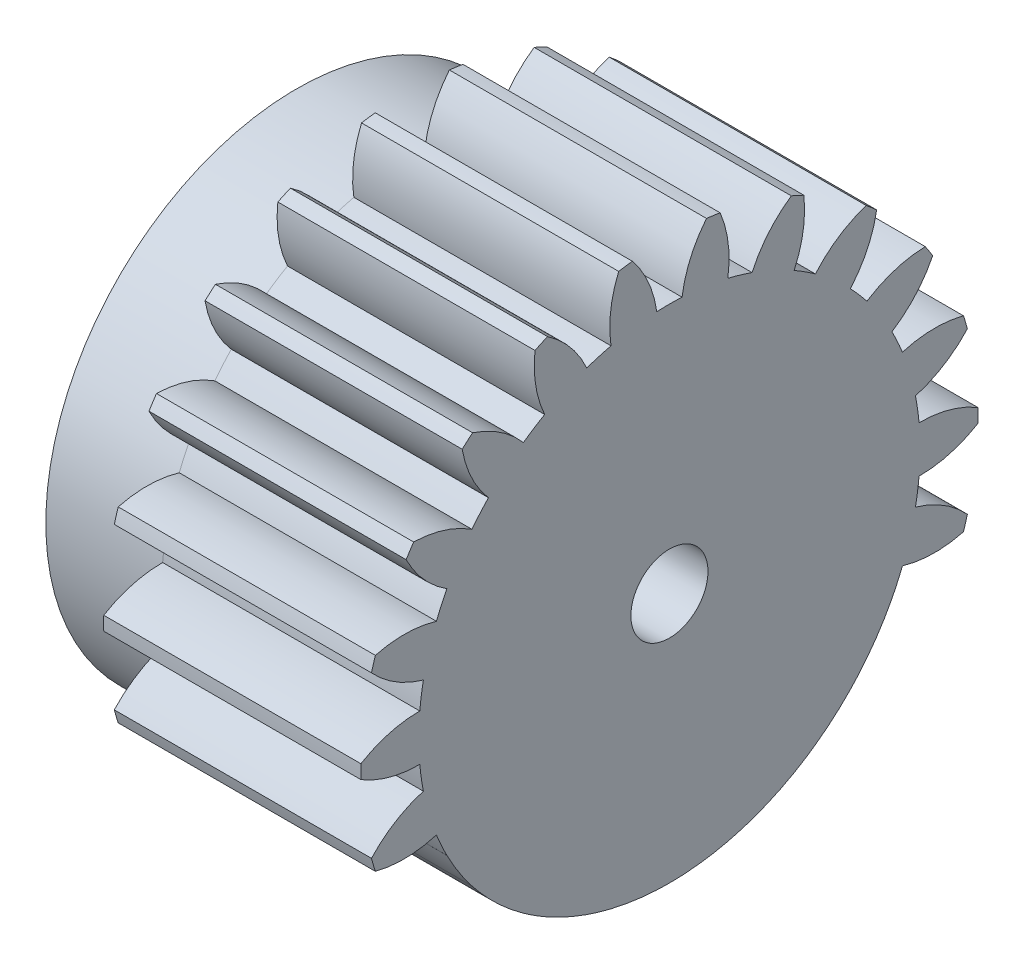
SolidWorks part; units mm, degrees
ref_plane "Front Plane" through (0, 0, 0) normal (0, 0, 1) x (1, 0, 0)
ref_plane "Top Plane" through (0, 0, 0) normal (0, 1, 0) x (1, 0, 0)
ref_plane "Right Plane" through (0, 0, 0) normal (1, 0, 0) x (0, 0, -1)
ref_plane "Plane2" through (4.0389, 0, 0) normal (1, 0, 0) x (0, 0, -1)
sketch "Sketch5" plane through (4.0389, 0, 0) normal (1, 0, 0) x (0, 0, -1)
  circle A0 centre (3.23, 4.4522) radius 1.5
  arc A1 (-8.767, 4.1839) -> (-6.4774, 3.5525) centre (-6.496, 7.9525) ccw
  arc A2 (-6.4774, 3.5525) -> (-6.3377, 2.5805) centre (3.23, 4.4522) ccw
  arc A3 (-6.3377, 2.5805) -> (-8.3567, 1.3296) centre (-5.1159, -1.6464) ccw
  arc A4 (-8.3567, 1.3296) -> (-8.2055, 0.8148) centre (3.23, 4.4522) ccw
  arc A5 (-8.2055, 0.8148) -> (-5.8308, 0.8541) centre (-7.0882, 5.0706) ccw
  arc A6 (-5.8308, 0.8541) -> (-5.4228, -0.0392) centre (3.23, 4.4522) ccw
  arc A7 (-5.4228, -0.0392) -> (-7.0076, -1.8082) centre (-3.0596, -3.7507) ccw
  arc A8 (-7.0076, -1.8082) -> (-6.7175, -2.2596) centre (3.23, 4.4522) ccw
  arc A9 (-6.7175, -2.2596) -> (-4.45, -1.5529) centre (-6.8444, 2.1386) ccw
  arc A10 (-4.45, -1.5529) -> (-3.807, -2.295) centre (3.23, 4.4522) ccw
  arc A11 (-3.807, -2.295) -> (-4.8292, -4.4389) centre (-0.4938, -5.1904) ccw
  arc A12 (-4.8292, -4.4389) -> (-4.4237, -4.7902) centre (3.23, 4.4522) ccw
  arc A13 (-4.4237, -4.7902) -> (-2.4471, -3.4733) centre (-5.7845, -0.606) ccw
  arc A14 (-2.4471, -3.4733) -> (-1.621, -4.0043) centre (3.23, 4.4522) ccw
  arc A15 (-1.621, -4.0043) -> (-1.9978, -6.3492) centre (2.3736, -5.8489) ccw
  arc A16 (-1.9978, -6.3492) -> (-1.5097, -6.5721) centre (3.23, 4.4522) ccw
  arc A17 (-1.5097, -6.5721) -> (0.0157, -4.7517) centre (-3.9943, -2.9408) ccw
  arc A18 (0.0157, -4.7517) -> (0.9579, -5.0284) centre (3.23, 4.4522) ccw
  arc A19 (0.9579, -5.0284) -> (1.257, -7.3845) centre (5.3105, -5.6729) ccw
  arc A20 (1.257, -7.3845) -> (1.7882, -7.4609) centre (3.23, 4.4522) ccw
  arc A21 (1.7882, -7.4609) -> (2.739, -5.2845) centre (-1.6189, -4.6766) ccw
  arc A22 (2.739, -5.2845) -> (3.721, -5.2845) centre (3.23, 4.4522) ccw
  arc A23 (3.721, -5.2845) -> (4.6718, -7.4609) centre (8.0788, -4.6766) ccw
  arc A24 (4.6718, -7.4609) -> (5.2029, -7.3845) centre (3.23, 4.4522) ccw
  arc A25 (5.2029, -7.3845) -> (5.502, -5.0284) centre (1.1494, -5.6729) ccw
  arc A26 (5.502, -5.0284) -> (6.4442, -4.7517) centre (3.23, 4.4522) ccw
  arc A27 (6.4442, -4.7517) -> (7.9696, -6.5721) centre (10.4542, -2.9408) ccw
  arc A28 (7.9696, -6.5721) -> (8.4577, -6.3492) centre (3.23, 4.4522) ccw
  arc A29 (8.4577, -6.3492) -> (8.0809, -4.0043) centre (4.0863, -5.8489) ccw
  arc A30 (8.0809, -4.0043) -> (8.907, -3.4733) centre (3.23, 4.4522) ccw
  arc A31 (8.907, -3.4733) -> (10.8836, -4.7902) centre (12.2444, -0.606) ccw
  arc A32 (10.8836, -4.7902) -> (11.2891, -4.4389) centre (3.23, 4.4522) ccw
  arc A33 (11.2891, -4.4389) -> (10.2669, -2.295) centre (6.9537, -5.1904) ccw
  arc A34 (10.2669, -2.295) -> (10.9099, -1.5529) centre (3.23, 4.4522) ccw
  arc A35 (10.9099, -1.5529) -> (13.1774, -2.2596) centre (13.3043, 2.1386) ccw
  arc A36 (13.1774, -2.2596) -> (13.4675, -1.8082) centre (3.23, 4.4522) ccw
  arc A37 (13.4675, -1.8082) -> (11.8827, -0.0392) centre (9.5195, -3.7507) ccw
  arc A38 (11.8827, -0.0392) -> (12.2907, 0.8541) centre (3.23, 4.4522) ccw
  arc A39 (12.2907, 0.8541) -> (14.6654, 0.8148) centre (13.5481, 5.0706) ccw
  arc A40 (14.6654, 0.8148) -> (14.8166, 1.3296) centre (3.23, 4.4522) ccw
  arc A41 (14.8166, 1.3296) -> (12.7976, 2.5805) centre (11.5758, -1.6464) ccw
  arc A42 (12.7976, 2.5805) -> (12.9374, 3.5525) centre (3.23, 4.4522) ccw
  arc A43 (12.9374, 3.5525) -> (15.227, 4.1839) centre (12.9559, 7.9525) ccw
  arc A44 (15.227, 4.1839) -> (15.227, 4.7205) centre (3.23, 4.4522) ccw
  arc A45 (15.227, 4.7205) -> (12.9374, 5.3518) centre (12.9559, 0.9519) ccw
  arc A46 (12.9374, 5.3518) -> (12.7976, 6.3238) centre (3.23, 4.4522) ccw
  arc A47 (12.7976, 6.3238) -> (14.8166, 7.5747) centre (11.5758, 10.5508) ccw
  arc A48 (14.8166, 7.5747) -> (14.6654, 8.0895) centre (3.23, 4.4522) ccw
  arc A49 (14.6654, 8.0895) -> (12.2907, 8.0503) centre (13.5481, 3.8338) ccw
  arc A50 (12.2907, 8.0503) -> (11.8827, 8.9435) centre (3.23, 4.4522) ccw
  arc A51 (11.8827, 8.9435) -> (13.4675, 10.7125) centre (9.5195, 12.655) ccw
  arc A52 (13.4675, 10.7125) -> (13.1774, 11.1639) centre (3.23, 4.4522) ccw
  arc A53 (13.1774, 11.1639) -> (10.9099, 10.4572) centre (13.3043, 6.7658) ccw
  arc A54 (10.9099, 10.4572) -> (10.2669, 11.1994) centre (3.23, 4.4522) ccw
  arc A55 (10.2669, 11.1994) -> (11.2891, 13.3432) centre (6.9537, 14.0947) ccw
  arc A56 (11.2891, 13.3432) -> (10.8836, 13.6946) centre (3.23, 4.4522) ccw
  arc A57 (10.8836, 13.6946) -> (8.907, 12.3777) centre (12.2444, 9.5103) ccw
  arc A58 (8.907, 12.3777) -> (8.0809, 12.9086) centre (3.23, 4.4522) ccw
  arc A59 (8.0809, 12.9086) -> (8.4577, 15.2536) centre (4.0863, 14.7533) ccw
  arc A60 (8.4577, 15.2536) -> (7.9696, 15.4765) centre (3.23, 4.4522) ccw
  arc A61 (7.9696, 15.4765) -> (6.4442, 13.6561) centre (10.4542, 11.8451) ccw
  arc A62 (6.4442, 13.6561) -> (5.502, 13.9327) centre (3.23, 4.4522) ccw
  arc A63 (5.502, 13.9327) -> (5.2029, 16.2889) centre (1.1494, 14.5772) ccw
  arc A64 (5.2029, 16.2889) -> (4.6718, 16.3652) centre (3.23, 4.4522) ccw
  arc A65 (4.6718, 16.3652) -> (3.721, 14.1888) centre (8.0788, 13.581) ccw
  arc A66 (3.721, 14.1888) -> (2.739, 14.1888) centre (3.23, 4.4522) ccw
  arc A67 (2.739, 14.1888) -> (1.7882, 16.3652) centre (-1.6189, 13.581) ccw
  arc A68 (1.7882, 16.3652) -> (1.257, 16.2889) centre (3.23, 4.4522) ccw
  arc A69 (1.257, 16.2889) -> (0.9579, 13.9327) centre (5.3105, 14.5772) ccw
  arc A70 (0.9579, 13.9327) -> (0.0157, 13.6561) centre (3.23, 4.4522) ccw
  arc A71 (0.0157, 13.6561) -> (-1.5097, 15.4765) centre (-3.9943, 11.8451) ccw
  arc A72 (-1.5097, 15.4765) -> (-1.9978, 15.2536) centre (3.23, 4.4522) ccw
  arc A73 (-1.9978, 15.2536) -> (-1.621, 12.9086) centre (2.3736, 14.7533) ccw
  arc A74 (-1.621, 12.9086) -> (-2.4471, 12.3777) centre (3.23, 4.4522) ccw
  arc A75 (-2.4471, 12.3777) -> (-4.4237, 13.6946) centre (-5.7845, 9.5103) ccw
  arc A76 (-4.4237, 13.6946) -> (-4.8292, 13.3432) centre (3.23, 4.4522) ccw
  arc A77 (-4.8292, 13.3432) -> (-3.807, 11.1994) centre (-0.4938, 14.0947) ccw
  arc A78 (-3.807, 11.1994) -> (-4.45, 10.4572) centre (3.23, 4.4522) ccw
  arc A79 (-4.45, 10.4572) -> (-6.7175, 11.1639) centre (-6.8444, 6.7658) ccw
  arc A80 (-6.7175, 11.1639) -> (-7.0076, 10.7125) centre (3.23, 4.4522) ccw
  arc A81 (-7.0076, 10.7125) -> (-5.4228, 8.9435) centre (-3.0596, 12.655) ccw
  arc A82 (-5.4228, 8.9435) -> (-5.8308, 8.0503) centre (3.23, 4.4522) ccw
  arc A83 (-5.8308, 8.0503) -> (-8.2055, 8.0895) centre (-7.0882, 3.8338) ccw
  arc A84 (-8.2055, 8.0895) -> (-8.3567, 7.5747) centre (3.23, 4.4522) ccw
  arc A85 (-8.3567, 7.5747) -> (-6.3377, 6.3238) centre (-5.1159, 10.5508) ccw
  arc A86 (-6.3377, 6.3238) -> (-6.4774, 5.3518) centre (3.23, 4.4522) ccw
  arc A87 (-6.4774, 5.3518) -> (-8.767, 4.7205) centre (-6.496, 0.9519) ccw
  arc A88 (-8.767, 4.7205) -> (-8.767, 4.1839) centre (3.23, 4.4522) ccw
extrude "Boss-Extrude1" add sketch "Sketch5" against normal blind 10 separate body
ref_plane "Plane3" through (0, 0, -3.23) normal (0, 0, 1) x (1, 0, 0)
sketch "Sketch10" plane through (0, 0, -3.23) normal (0, 0, 1) x (1, 0, 0)
  line L0 (-5.9611, 7.9022) -> (-5.9611, 14.2022)
  line L1 (-5.9611, 14.2022) -> (-10.4611, 14.2022)
  line L2 (-10.4611, 14.2022) -> (-10.4611, 7.9022)
  line L3 (-10.4611, 7.9022) -> (-5.9611, 7.9022)
  line L4 (-10.4611, 4.4522) -> (-5.9611, 4.4522) construction
revolve "Revolve2" add sketch "Sketch10" angle 360 about L4
sketch "Sketch11" plane through (4.0389, 0, 0) normal (1, 0, 0) x (0, 0, -1)
  line L1 (-8.5483, 0.266) -> (-5.5756, 0.266)
  line L2 (12.0356, 0.266) -> (15.0082, 0.266)
  arc A0 (-5.5756, 0.266) -> (12.0356, 0.266) centre (3.23, 4.4522) ccw
  arc A1 (-8.5483, 0.266) -> (15.0082, 0.266) centre (3.23, 4.4522) ccw
  point P1 (-8.5483, 0.266)
  dimension "D1" = 19.5
  dimension "D2" = 25
extrude "Cut-Extrude1" cut sketch "Sketch11" against normal blind 10
sketch "Sketch13" plane through (-10.4611, 0, 0) normal (-1, 0, 0) x (0, 0, 1)
  circle A0 centre (-3.23, 4.4522) radius 4.1
  dimension "D1" = 8.2
extrude "Cut-Extrude2" cut sketch "Sketch13" against normal up to surface (4.5 mm away) up to face at (-5.9611, 4.4522, -4.73)
sketch "Sketch14" plane through (-5.9611, 0, 0) normal (-1, 0, 0) x (0, 0, 1)
  circle A0 centre (-3.23, 4.4522) radius 3.25
  dimension "D1" = 6.5
extrude "Cut-Extrude3" cut sketch "Sketch14" against normal blind 3
